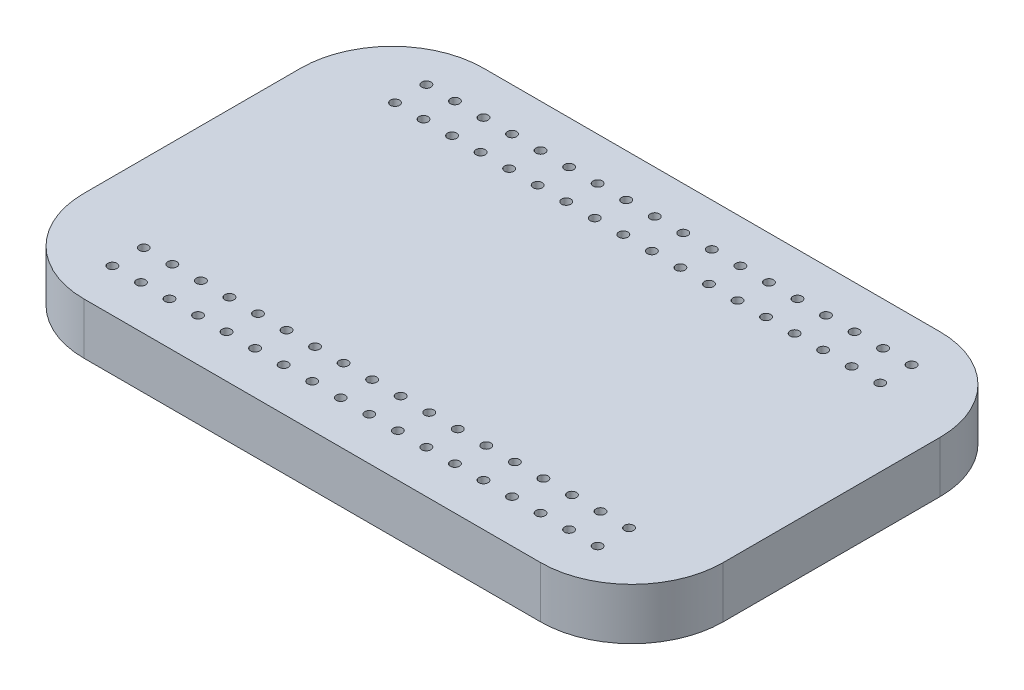
SolidWorks part; units mm, degrees
ref_plane "Front Plane" through (0, 0, 0) normal (0, 0, 1) x (1, 0, 0)
ref_plane "Top Plane" through (0, 0, 0) normal (0, 1, 0) x (1, 0, 0)
ref_plane "Right Plane" through (0, 0, 0) normal (1, 0, 0) x (0, 0, -1)
sketch "Sketch1" plane through (0, 0, 0) normal (0, 1, 0) x (1, 0, 0)
  line L0 (-28, 17.5) -> (28, -17.5) construction
  line L1 (-28, 17.5) -> (28, 17.5)
  line L2 (-28, 17.5) -> (-28, -17.5)
  line L3 (-28, -17.5) -> (28, -17.5)
  line L4 (28, 17.5) -> (28, -17.5)
  line L5 (0, 0) -> (28, 17.5) construction
  point P5 (0, 0)
  dimension "D1" = 35
  dimension "D2" = 56
extrude "Boss-Extrude1" add sketch "Sketch1" along normal mid plane 4.5 contours L3 L4 L1 L2
fillet "Fillet1" radius 8 4 edges at (28, 0, -17.5) (-28, 0, -17.5) (-28, 0, 17.5) (28, 0, 17.5)
sketch "Sketch2" plane through (0, 2.25, 0) normal (0, 1, 0) x (1, 0, 0)
  circle A0 centre (21.25, 11) radius 0.4
  circle A1 centre (21.25, 13.75) radius 0.4
  circle A2 centre (21.25, -11) radius 0.4
  circle A3 centre (21.25, -13.75) radius 0.4
  point P8 (0, 0)
  dimension "D1" = 0.8
  dimension "D2" = 22
  dimension "D3" = 27.5
  dimension "D4" = 2.75
  dimension "D5" = 11
  dimension "D6" = 21.25
extrude "Cut-Extrude1" cut sketch "Sketch2" against normal through all
pattern_linear "LPattern1" count 18 spacing 2.5 along (-1, 0, 0) of "Cut-Extrude1"
equation "\"D4@Sketch2\"=(\"D3@Sketch2\"-\"D2@Sketch2\")/2"
equation "\"D5@Sketch2\"=\"D2@Sketch2\"/2"
